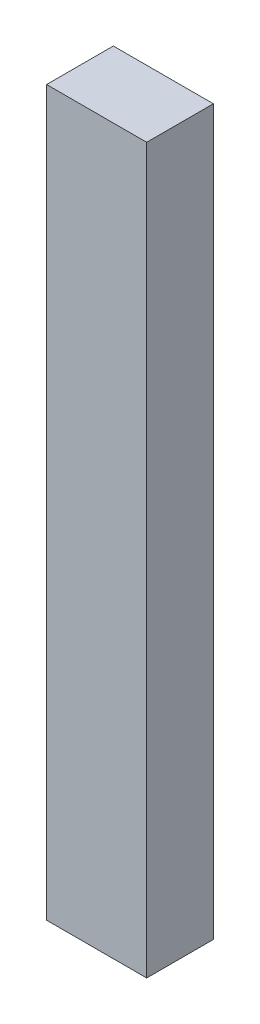
SolidWorks part; units mm, degrees
ref_plane "Front Plane" through (0, 0, 0) normal (0, 0, 1) x (1, 0, 0)
ref_plane "Top Plane" through (0, 0, 0) normal (0, 1, 0) x (1, 0, 0)
ref_plane "Right Plane" through (0, 0, 0) normal (1, 0, 0) x (0, 0, -1)
sketch "Sketch1" plane through (0, 0, 0) normal (0, 1, 0) x (1, 0, 0)
  line L1 (-47.4737, 7.1842) -> (-17.4737, 7.1842)
  line L2 (-47.4737, 7.1842) -> (-47.4737, -12.8158)
  line L3 (-47.4737, -12.8158) -> (-17.4737, -12.8158)
  line L4 (-17.4737, 7.1842) -> (-17.4737, -12.8158)
  dimension "D1" = 30
  dimension "D2" = 20
extrude "Boss-Extrude1" add sketch "Sketch1" along normal blind 217
